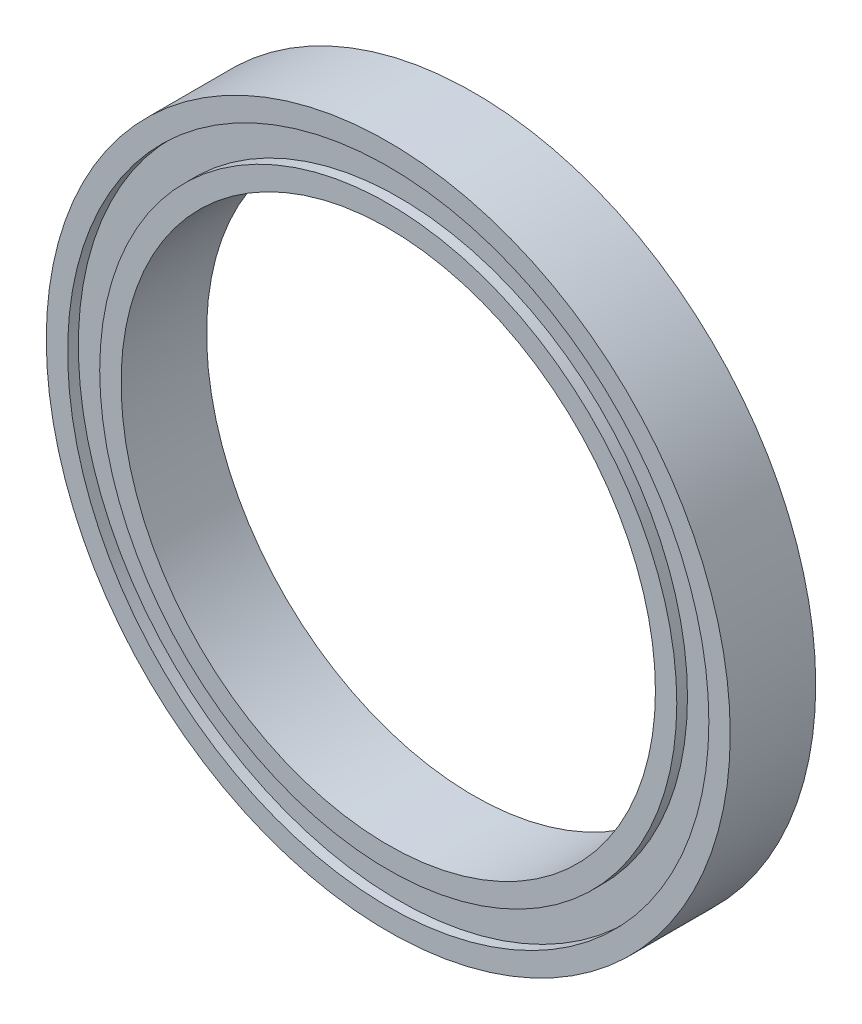
SolidWorks part; units mm, degrees
ref_plane "Front Plane" through (0, 0, 0) normal (0, 0, 1) x (1, 0, 0)
ref_plane "Top Plane" through (0, 0, 0) normal (0, 1, 0) x (1, 0, 0)
ref_plane "Right Plane" through (0, 0, 0) normal (1, 0, 0) x (0, 0, -1)
sketch "Sketch1" plane through (0, 0, 0) normal (0, 0, 1) x (1, 0, 0)
  circle A0 centre (0, 0) radius 12.5
  circle A1 centre (0, 0) radius 13.5
  circle A2 centre (0, 0) radius 15
  circle A3 centre (0, 0) radius 16
  dimension "D1" = 32
  dimension "D2" = 25
  dimension "D3" = 1
  dimension "D4" = 1
extrude "Boss-Extrude1" add sketch "Sketch1" along normal blind 4 contours A1 A0 | A3 A2
sketch "Sketch2" plane through (0, 0, 4) normal (0, 0, 1) x (1, 0, 0)
  circle A0 centre (0, 0) radius 13.5 construction
  circle A1 centre (0, 0) radius 15 construction
  circle A2 centre (0, 0) radius 13.5
  circle A3 centre (0, 0) radius 15
extrude "Boss-Extrude2" add sketch "Sketch2" against normal blind 3 from offset 0.5 offset against normal yes
